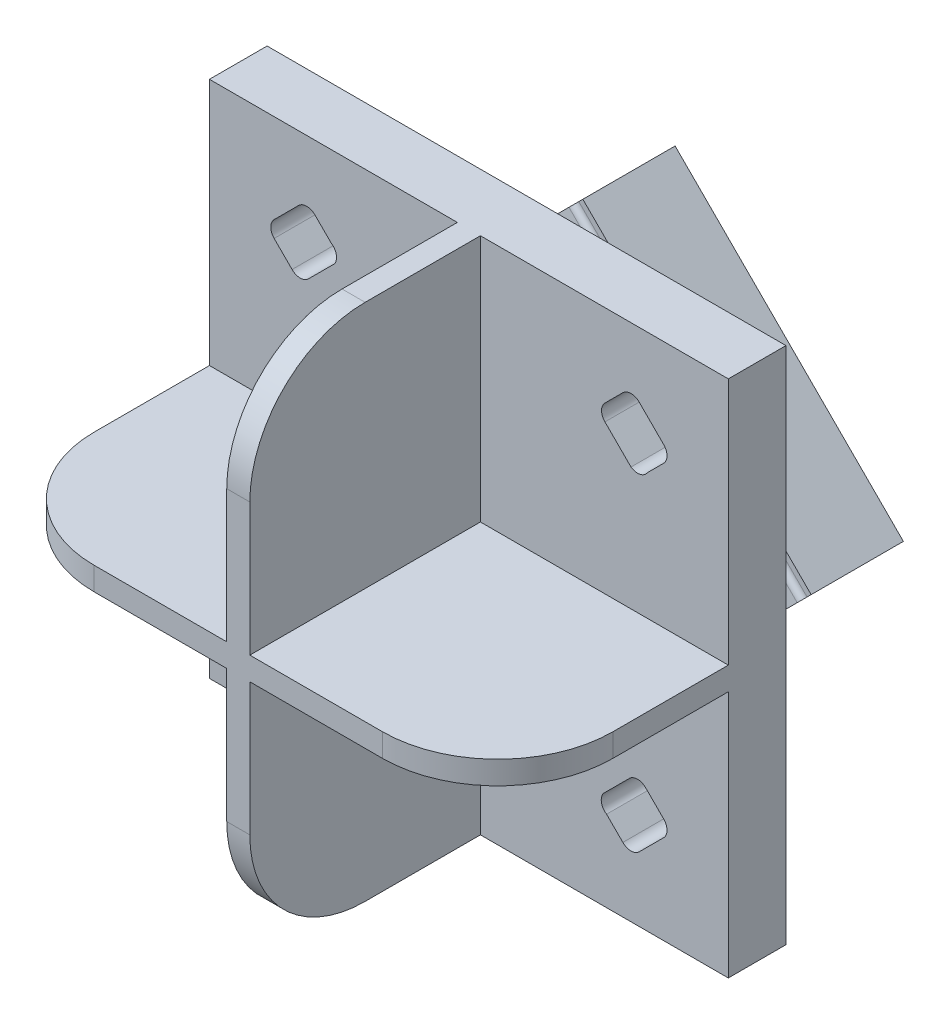
SolidWorks part; units mm, degrees
ref_plane "Plan de face" through (0, 0, 0) normal (0, 0, 1) x (1, 0, 0)
ref_plane "Plan de dessus" through (0, 0, 0) normal (0, 1, 0) x (1, 0, 0)
ref_plane "Plan de droite" through (0, 0, 0) normal (1, 0, 0) x (0, 0, -1)
sketch "Esquisse1" plane through (0, 0, 0) normal (0, 0, 1) x (1, 0, 0)
  line L0 (14.7679, 16.8893) -> (16.8893, 14.7679)
  line L1 (-22.5, 22.5) -> (22.5, 22.5)
  line L2 (-22.5, 22.5) -> (-22.5, -22.5)
  line L3 (-22.5, -22.5) -> (22.5, -22.5)
  line L4 (22.5, 22.5) -> (22.5, -22.5)
  line L5 (-22.5, 22.5) -> (22.5, -22.5) construction
  line L6 (-22.5, -22.5) -> (22.5, 22.5) construction
  line L7 (11.7981, 13.9194) -> (14.0608, 11.6567)
  line L8 (13.3537, 16.8893) -> (11.7981, 15.3336)
  line L9 (15.4751, 11.9395) -> (16.8893, 13.3537)
  line L10 (11.9395, -15.4751) -> (13.3537, -16.8893)
  line L11 (16.8893, -14.7679) -> (14.7679, -16.8893)
  line L12 (16.8893, -13.3537) -> (15.3336, -11.7981)
  line L13 (13.9194, -11.7981) -> (11.6567, -14.0608)
  line L14 (-15.4751, -11.9395) -> (-16.8893, -13.3537)
  line L15 (-14.7679, -16.8893) -> (-16.8893, -14.7679)
  line L16 (-13.3537, -16.8893) -> (-11.7981, -15.3336)
  line L17 (-11.7981, -13.9194) -> (-14.0608, -11.6567)
  line L18 (-11.9395, 15.4751) -> (-13.3537, 16.8893)
  line L19 (-16.8893, 14.7679) -> (-14.7679, 16.8893)
  line L20 (-16.8893, 13.3537) -> (-15.3336, 11.7981)
  line L21 (-13.9194, 11.7981) -> (-11.6567, 14.0608)
  arc A0 (11.7981, 13.9194) -> (11.7981, 15.3336) centre (12.5052, 14.6265) cw
  arc A1 (14.0608, 11.6567) -> (15.4751, 11.9395) centre (14.6321, 12.4775) ccw
  arc A2 (16.8893, 14.7679) -> (16.8893, 13.3537) centre (16.1822, 14.0608) cw
  arc A3 (14.7679, 16.8893) -> (13.3537, 16.8893) centre (14.0608, 16.1822) ccw
  arc A4 (14.7679, -16.8893) -> (13.3537, -16.8893) centre (14.0608, -16.1822) cw
  arc A5 (11.6567, -14.0608) -> (11.9395, -15.4751) centre (12.4775, -14.6321) ccw
  arc A6 (16.8893, -14.7679) -> (16.8893, -13.3537) centre (16.1822, -14.0608) ccw
  arc A7 (13.9194, -11.7981) -> (15.3336, -11.7981) centre (14.6265, -12.5052) cw
  arc A8 (-16.8893, -14.7679) -> (-16.8893, -13.3537) centre (-16.1822, -14.0608) cw
  arc A9 (-14.0608, -11.6567) -> (-15.4751, -11.9395) centre (-14.6321, -12.4775) ccw
  arc A10 (-14.7679, -16.8893) -> (-13.3537, -16.8893) centre (-14.0608, -16.1822) ccw
  arc A11 (-11.7981, -13.9194) -> (-11.7981, -15.3336) centre (-12.5052, -14.6265) cw
  arc A12 (-14.7679, 16.8893) -> (-13.3537, 16.8893) centre (-14.0608, 16.1822) cw
  arc A13 (-11.6567, 14.0608) -> (-11.9395, 15.4751) centre (-12.4775, 14.6321) ccw
  arc A14 (-16.8893, 14.7679) -> (-16.8893, 13.3537) centre (-16.1822, 14.0608) ccw
  arc A15 (-13.9194, 11.7981) -> (-15.3336, 11.7981) centre (-14.6265, 12.5052) cw
  point P0 (0, 0)
  point P14 (10.949, 14.626)
  point P58 (0, 0)
  dimension "D7" = 2.5
  dimension "D8" = 2.5
  dimension "D3" = 1
  dimension "D1" = 45
  dimension "D2" = 45
  dimension "D4" = 4
  dimension "D5" = 3
  dimension "D6" = 2
extrude "Boss.-Extru.1" add sketch "Esquisse1" along normal blind 5
sketch "Esquisse2" plane through (0, 0, 5) normal (0, 0, 1) x (1, 0, 0)
  line L0 (-1, 22.5) -> (-1, 1)
  line L1 (22.5, 22.5) -> (-22.5, 22.5) construction
  line L2 (-1, 1) -> (-22.5, 1)
  line L3 (-22.5, 22.5) -> (-22.5, -22.5) construction
  line L4 (-22.5, 1) -> (-22.5, -1)
  line L5 (-22.5, -1) -> (-1, -1)
  line L6 (-1, -1) -> (-1, -22.5)
  line L7 (-22.5, -22.5) -> (22.5, -22.5) construction
  line L8 (-1, -22.5) -> (1, -22.5)
  line L9 (1, -22.5) -> (1, -1)
  line L10 (1, -1) -> (22.5, -1)
  line L11 (22.5, -22.5) -> (22.5, 22.5) construction
  line L12 (22.5, -1) -> (22.5, 1)
  line L13 (22.5, 1) -> (1, 1)
  line L14 (1, 1) -> (1, 22.5)
  line L15 (1, 22.5) -> (-1, 22.5)
  dimension "D1" = 2
  dimension "D2" = 2
  dimension "D3" = 2
  dimension "D4" = 2
  dimension "D5" = 1
  dimension "D6" = 1
  dimension "D7" = 1
extrude "Boss.-Extru.2" add sketch "Esquisse2" along normal blind 20
sketch "Esquisse3" plane through (0, 0, 0) normal (0, 0, -1) x (-1, 0, 0)
  line L0 (-20.6829, 0.8839) -> (-0.8839, 20.6829)
  line L1 (-0.8839, 20.6829) -> (20.6829, -0.8839)
  line L2 (20.6829, -0.8839) -> (0.8839, -20.6829)
  line L3 (0.8839, -20.6829) -> (-20.6829, 0.8839)
  dimension "D1" = 28
  dimension "D2" = 14
  dimension "D3" = 30.5
  dimension "D4" = 15.25
extrude "Boss.-Extru.3" add sketch "Esquisse3" along normal blind 12
fillet "Congé1" radius 10 4 edges at (0, 22.5, 25) (22.5, 0, 25) (0, -22.5, 25) (-22.5, 0, 25)
sketch "Esquisse4" plane through (10.7834, 10.7834, 0) normal (0.7071, 0.7071, 0) x (0, 0, -1)
  line L0 (0, 14) -> (4, 14)
  line L1 (0, 14) -> (0, -17.3835)
  line L2 (4, 14) -> (4, -17.3835)
  line L3 (0, -17.3835) -> (4, -17.3835)
  line L5 (0, 0) -> (0, 31.8198) construction
  dimension "D1" = 4
extrude "Enlèv. mat.-Extru.1" cut sketch "Esquisse4" against normal blind 1
sketch "Esquisse5" plane through (0, 0, 0) normal (0, 0, -1) x (-1, 0, 0)
  line L0 (22.5, 22.5) -> (-22.5, -22.5) construction
sketch "Esquisse6" plane through (-10.7834, -10.7834, 0) normal (-0.7071, -0.7071, 0) x (0, 0, 1)
  line L0 (0, 14) -> (-4, 14)
  line L1 (0, 14) -> (0, -14.2425)
  line L2 (-4, 14) -> (-4, -14.2425)
  line L3 (0, -14.2425) -> (-4, -14.2425)
ref_plane "Plan3" through (-20.6829, -0.8839, 0) normal (0, 0, 1) x (1, 0, 0)
extrude "Enlèv. mat.-Extru.2" cut sketch "Esquisse6" against normal blind 1
fillet "Congé2" radius 1 4 edges at (-10.0763, -10.0763, 0) (9.8995, -9.8995, 0) (10.0763, 10.0763, 0) (-9.8995, 9.8995, 0)
fillet "Congé3" radius 0.5 2 edges at (-10.0763, -10.0763, -4) (10.0763, 10.0763, -4)
